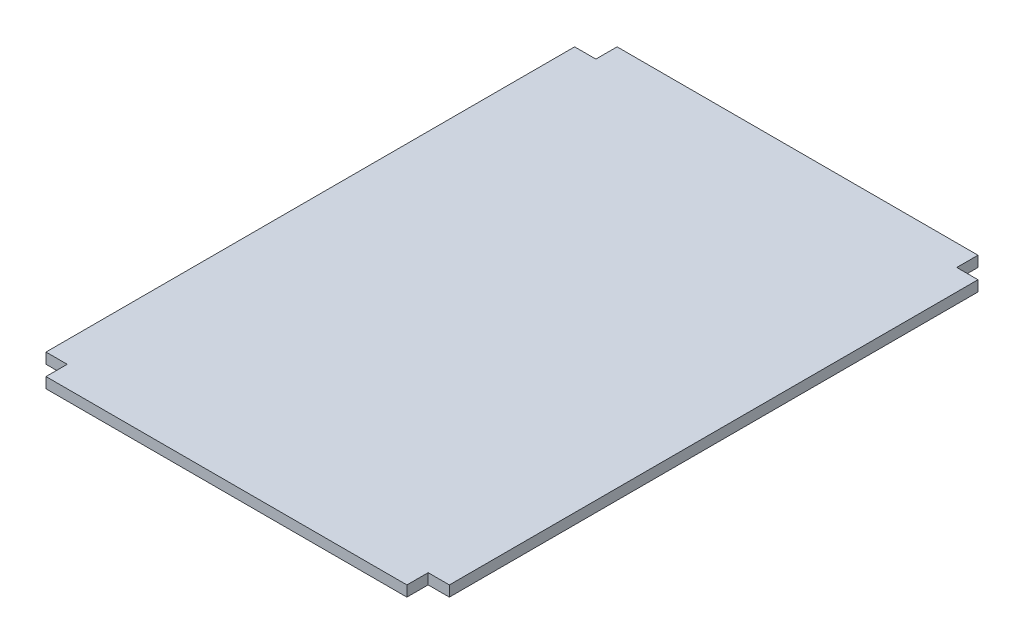
SolidWorks part; units mm, degrees
material "Oak"
ref_plane "Front Plane" through (0, 0, 0) normal (0, 0, 1) x (1, 0, 0)
ref_plane "Top Plane" through (0, 0, 0) normal (0, 1, 0) x (1, 0, 0)
ref_plane "Right Plane" through (0, 0, 0) normal (1, 0, 0) x (0, 0, -1)
sketch "Sketch1" plane through (0, 0, 0) normal (0, 1, 0) x (1, 0, 0)
  line L0 (0, 341.63) -> (0, -341.63) construction
  line L1 (-241.3, -341.63) -> (241.3, -341.63)
  line L2 (-241.3, -341.63) -> (-241.3, 341.63)
  line L3 (-241.3, 341.63) -> (241.3, 341.63)
  line L4 (241.3, -341.63) -> (241.3, 341.63)
  line L5 (-241.3, -341.63) -> (241.3, 341.63) construction
  line L6 (-241.3, 341.63) -> (241.3, -341.63) construction
  line L7 (-241.3, 341.63) -> (-215.9, 341.63)
  line L8 (-241.3, 341.63) -> (-241.3, 316.23)
  line L9 (-241.3, 316.23) -> (-215.9, 316.23)
  line L10 (-215.9, 341.63) -> (-215.9, 316.23)
  line L11 (-241.3, 0) -> (241.3, 0) construction
  line L12 (241.3, 316.23) -> (215.9, 316.23)
  line L13 (215.9, 341.63) -> (215.9, 316.23)
  line L14 (241.3, -316.23) -> (215.9, -316.23)
  line L15 (215.9, -341.63) -> (215.9, -316.23)
  line L16 (-215.9, -341.63) -> (-215.9, -316.23)
  line L17 (-241.3, -316.23) -> (-215.9, -316.23)
  point P0 (0, 0)
  dimension "D1" = 482.6
  dimension "D2" = 683.26
  dimension "D3" = 25.4
extrude "Boss-Extrude1" add sketch "Sketch1" along normal blind 12.7 contours L2 L17 L16 L1 L15 L14 L4 L12 L13 L3 L10 L9
